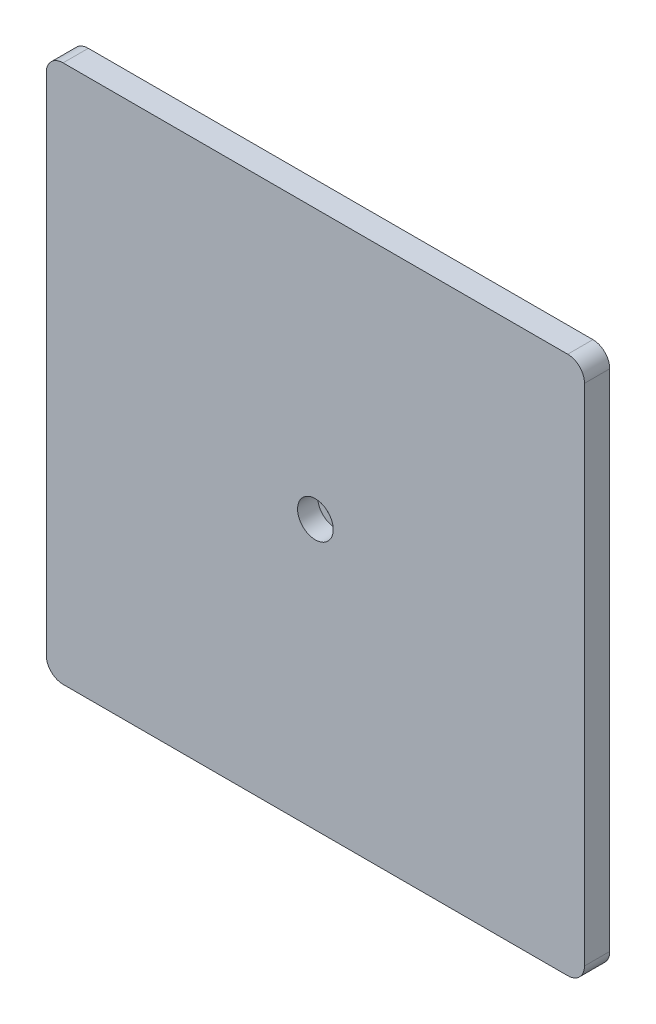
SolidWorks part; units mm, degrees
material "Cedar"
ref_plane "Plan de face" through (0, 0, 0) normal (0, 0, 1) x (1, 0, 0)
ref_plane "Plan de dessus" through (0, 0, 0) normal (0, 1, 0) x (1, 0, 0)
ref_plane "Plan de droite" through (0, 0, 0) normal (1, 0, 0) x (0, 0, -1)
sketch "Sketch1" plane through (0, 0, 0) normal (0, 0, 1) x (1, 0, 0)
  line L1 (-150, 160) -> (150, 160)
  line L2 (-160, 150) -> (-160, -150)
  line L3 (-150, -160) -> (150, -160)
  line L4 (160, 150) -> (160, -150)
  line L5 (-160, 160) -> (160, -160) construction
  line L6 (-160, -160) -> (160, 160) construction
  arc A0 (-160, -150) -> (-150, -160) centre (-150, -150) ccw
  arc A1 (150, -160) -> (160, -150) centre (150, -150) ccw
  arc A2 (150, 160) -> (160, 150) centre (150, 150) cw
  arc A3 (-150, 160) -> (-160, 150) centre (-150, 150) ccw
  point P0 (0, 0)
  dimension "D2" = 10
  dimension "D1" = 320
extrude "Boss-Extrude1" add sketch "Sketch1" along normal blind 15
sketch "Sketch2" plane through (0, 0, 15) normal (0, 0, 1) x (1, 0, 0)
  circle A0 centre (0, 0) radius 10.6
  dimension "D1" = 21.2
extrude "Cut-Extrude1" cut sketch "Sketch2" against normal blind 12
sketch "Sketch3" plane through (0, 0, 3) normal (0, 0, 1) x (1, 0, 0)
  circle A0 centre (0, 0) radius 6.5
  dimension "D1" = 13
extrude "Cut-Extrude2" cut sketch "Sketch3" against normal blind 10
sketch "Sketch4" plane through (0, 0, 15) normal (0, 0, 1) x (1, 0, 0)
  circle A0 centre (0, 25) radius 2
  circle A1 centre (25, 0) radius 2
  circle A2 centre (0, -25) radius 2
  circle A3 centre (-25, 0) radius 2
  dimension "D5" = 4
  dimension "D1" = 25
  dimension "D2" = 25
  dimension "D3" = 25
  dimension "D4" = 25
